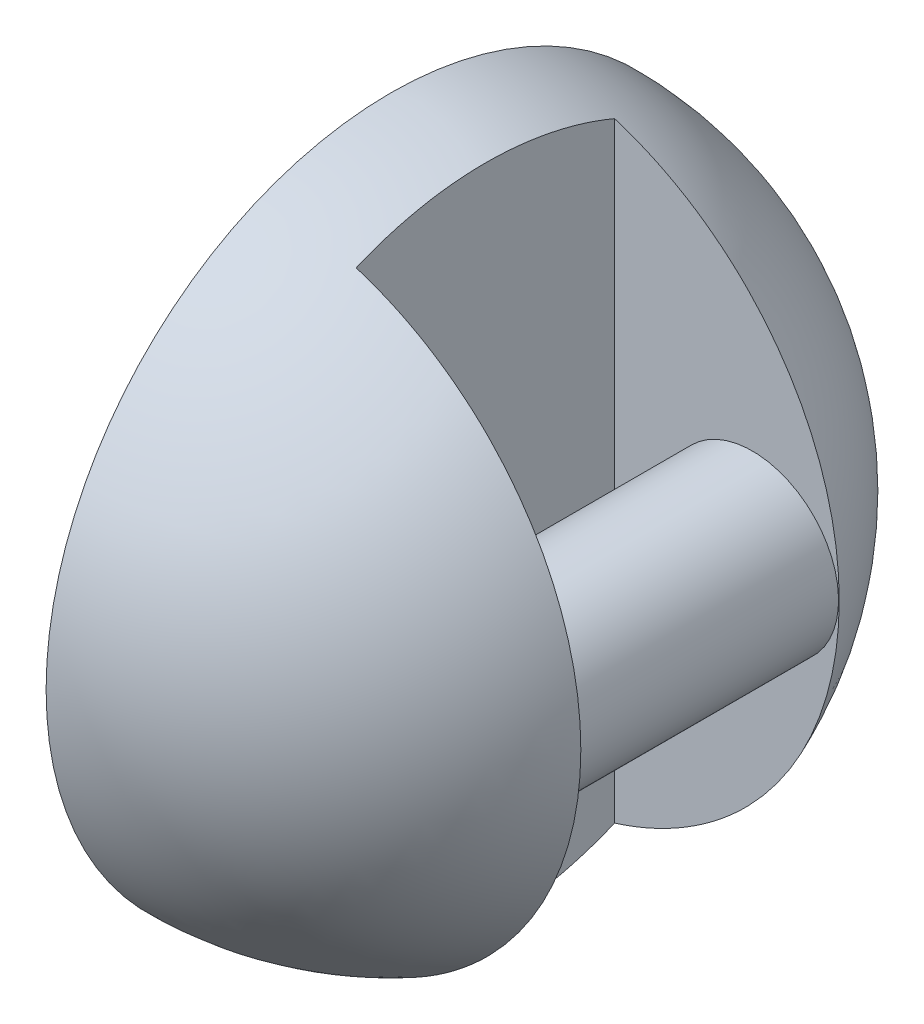
SolidWorks part; units mm, degrees
ref_plane "Front Plane" through (0, 0, 0) normal (0, 0, 1) x (1, 0, 0)
ref_plane "Top Plane" through (0, 0, 0) normal (0, 1, 0) x (1, 0, 0)
ref_plane "Right Plane" through (0, 0, 0) normal (1, 0, 0) x (0, 0, -1)
sketch "Sketch2" plane through (0, 0, 0) normal (1, 0, 0) x (0, 0, -1)
  circle A0 centre (0, 0) radius 20
  dimension "D1" = 40
sketch "Sketch3" plane through (0, 0, 0) normal (0, 0, 1) x (1, 0, 0)
  line L0 (0, 20) -> (0, -20)
  arc A0 (0, -20) -> (0, 20) centre (0, 0) ccw
  dimension "D1" = 40
revolve "Revolve1" add sketch "Sketch3" angle 360 about L0
extrude "Cut-Extrude1" cut sketch "Sketch2" against normal blind 30
ref_plane "Plane2" through (20, 0, 0) normal (1, 0, 0) x (0, 0, -1)
sketch "Sketch9" plane through (20, 0, 0) normal (1, 0, 0) x (0, 0, -1)
  line L1 (-7.5, 20.5) -> (7.5, 20.5)
  line L2 (-7.5, 20.5) -> (-7.5, -20.5)
  line L3 (-7.5, -20.5) -> (7.5, -20.5)
  line L4 (7.5, 20.5) -> (7.5, -20.5)
  dimension "D1" = 15
  dimension "D2" = 7.5
  dimension "D3" = 41
  dimension "D4" = 20.5
extrude "Cut-Extrude4" cut sketch "Sketch9" against normal blind 14.5
sketch "Sketch10" plane through (0, 0, 7.5) normal (0, 0, -1) x (-1, 0, 0)
  line L0 (-5.5, 19.2289) -> (-5.5, 17.7059) construction
  circle A0 centre (-13.5, 0) radius 5
  dimension "D1" = 10
  dimension "D2" = 8
extrude "Boss-Extrude2" add sketch "Sketch10" along normal blind 15
sketch "Sketch11" plane through (0, 0, 0) normal (-1, 0, 0) x (0, 0, 1)
  circle A0 centre (0, 0) radius 5
  dimension "D1" = 10
extrude "Cut-Extrude5" cut sketch "Sketch11" against normal blind 5
